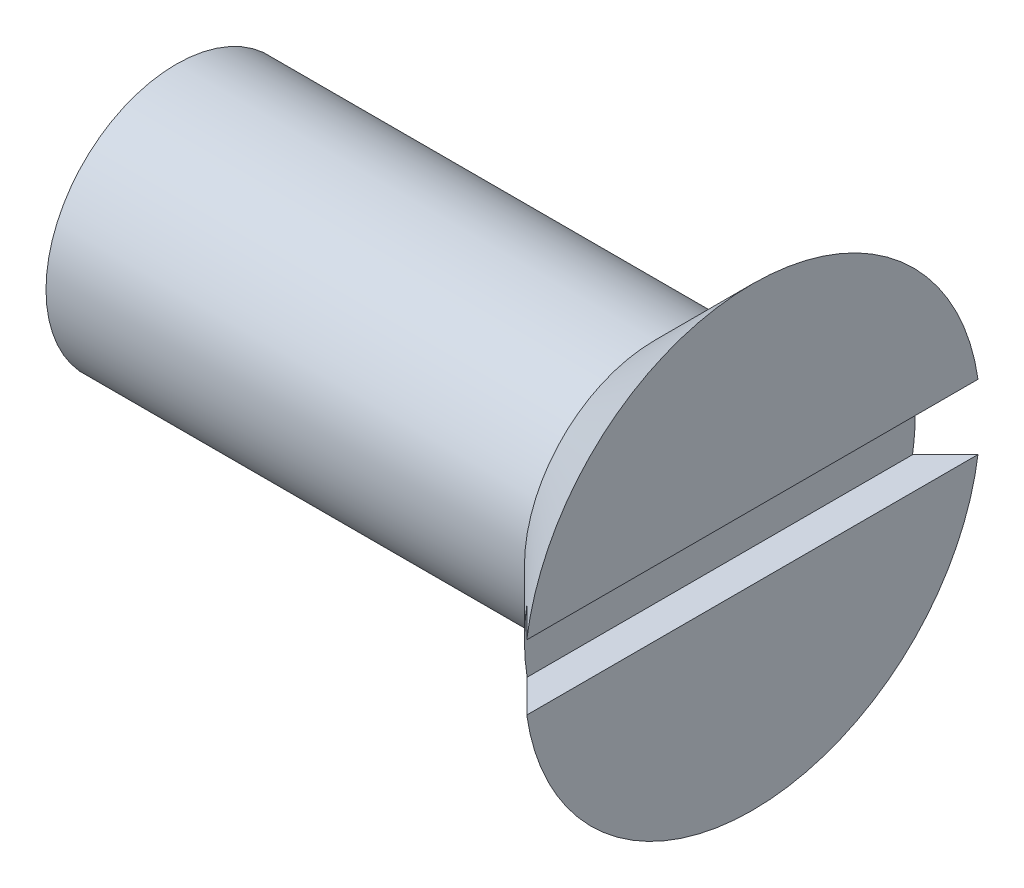
SolidWorks part; units mm, degrees
material "Gray Cast Iron"
ref_plane "Front Plane" through (0, 0, 0) normal (0, 0, 1) x (1, 0, 0)
ref_plane "Top Plane" through (0, 0, 0) normal (0, 1, 0) x (1, 0, 0)
ref_plane "Right Plane" through (0, 0, 0) normal (1, 0, 0) x (0, 0, -1)
sketch "Sketch1" plane through (0, 0, 0) normal (0, 0, 1) x (1, 0, 0)
  line L0 (0, 0) -> (-68057.6327, 0) construction
  line L1 (0, 0) -> (0, -68057.6327) construction
  line L2 (0, 0) -> (-20, 0)
  line L3 (-20, 0) -> (-17.6906, -4)
  line L4 (-17.6906, -4) -> (-3, -4)
  line L5 (-3, -4) -> (0, -7)
  line L6 (0, -7) -> (0, 0)
  dimension "D1" = 8
  dimension "D2" = 20
  dimension "D3" = 45
  dimension "D4" = 3
  dimension "D5" = 60
revolve "Revolve1" add sketch "Sketch1" angle 360 about L0
sketch "Sketch2" plane through (0, 0, 0) normal (1, 0, 0) x (0, 0, -1)
  line L1 (-7, 1) -> (7, 1)
  line L2 (-7, 1) -> (-7, -1)
  line L3 (-7, -1) -> (7, -1)
  line L4 (7, 1) -> (7, -1)
  line L5 (-7, 1) -> (7, -1) construction
  line L6 (-7, -1) -> (7, 1) construction
  circle A0 centre (0, 0) radius 7 construction
  point P0 (0, 0)
  dimension "D1" = 2
extrude "Cut-Extrude1" cut sketch "Sketch2" against normal blind 1
